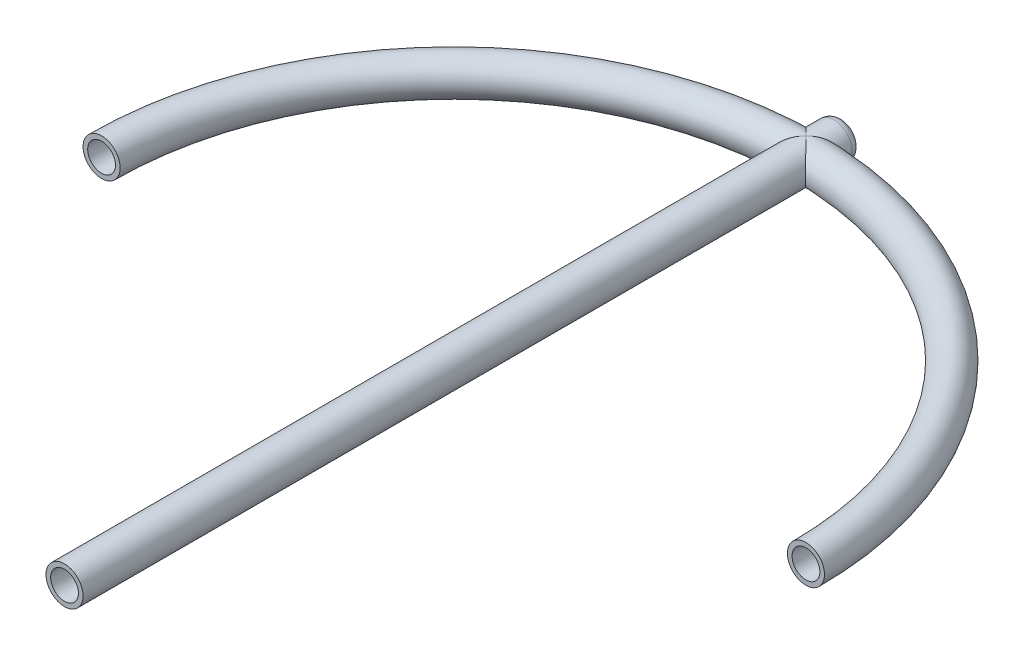
SolidWorks part; units mm, degrees
ref_plane "Front Plane" through (0, 0, 0) normal (0, 0, 1) x (1, 0, 0)
ref_plane "Top Plane" through (0, 0, 0) normal (0, 1, 0) x (1, 0, 0)
ref_plane "Right Plane" through (0, 0, 0) normal (1, 0, 0) x (0, 0, -1)
sketch "Sketch1" plane through (0, 0, 0) normal (0, 0, 1) x (1, 0, 0)
  circle A0 centre (-19, 0) radius 0.75
  circle A1 centre (-19, 0) radius 1
  circle A2 centre (19, 0) radius 0.75
  circle A3 centre (19, 0) radius 1
  dimension "D1" = 19
  dimension "D3" = 2
  dimension "D4" = 1.5
  dimension "D5" = 2
  dimension "D6" = 1.5
  dimension "D2" = 19
sketch "Sketch4" plane through (0, 0, 0) normal (0, 1, 0) x (1, 0, 0)
  line L2 (-20, 0) -> (-18, 0) construction
  line L3 (18.25, 0) -> (19.75, 0) construction
  arc A0 (-19, 0) -> (19, 0) centre (0, 0) cw
sweep "Sweep2" add profiles "Sketch1" path "Sketch4"
sketch "Sketch8" plane through (0, 0, 0) normal (1, 0, 0) x (0, 0, -1)
  line L1 (0, -1) -> (-20.4596, -1)
  line L2 (0, -1) -> (0, 1.066)
  line L3 (0, 1.066) -> (-20.4596, 1.066)
  line L4 (-20.4596, -1) -> (-20.4596, 1.066)
extrude "Cut-Extrude1" cut sketch "Sketch8" against normal through all both and the other way through all
sketch "Sketch9" plane through (0, 0, 0) normal (0, 0, 1) x (1, 0, 0)
  circle A0 centre (0, 0) radius 0.75
  circle A1 centre (0, 0) radius 1
  dimension "D1" = 1.5
  dimension "D2" = 2
extrude "Boss-Extrude1" add sketch "Sketch9" against normal blind 21 and the other way blind 21
sketch "Sketch10" plane through (0, 0, -21) normal (0, 0, -1) x (-1, 0, 0)
  circle A0 centre (0, 0) radius 0.75
extrude "Boss-Extrude4" add sketch "Sketch10" against normal blind 2
fillet "Fillet3" radius 0.5 1 edges at (1, 0, -21)
equation "\".5.00mm\"=1"
